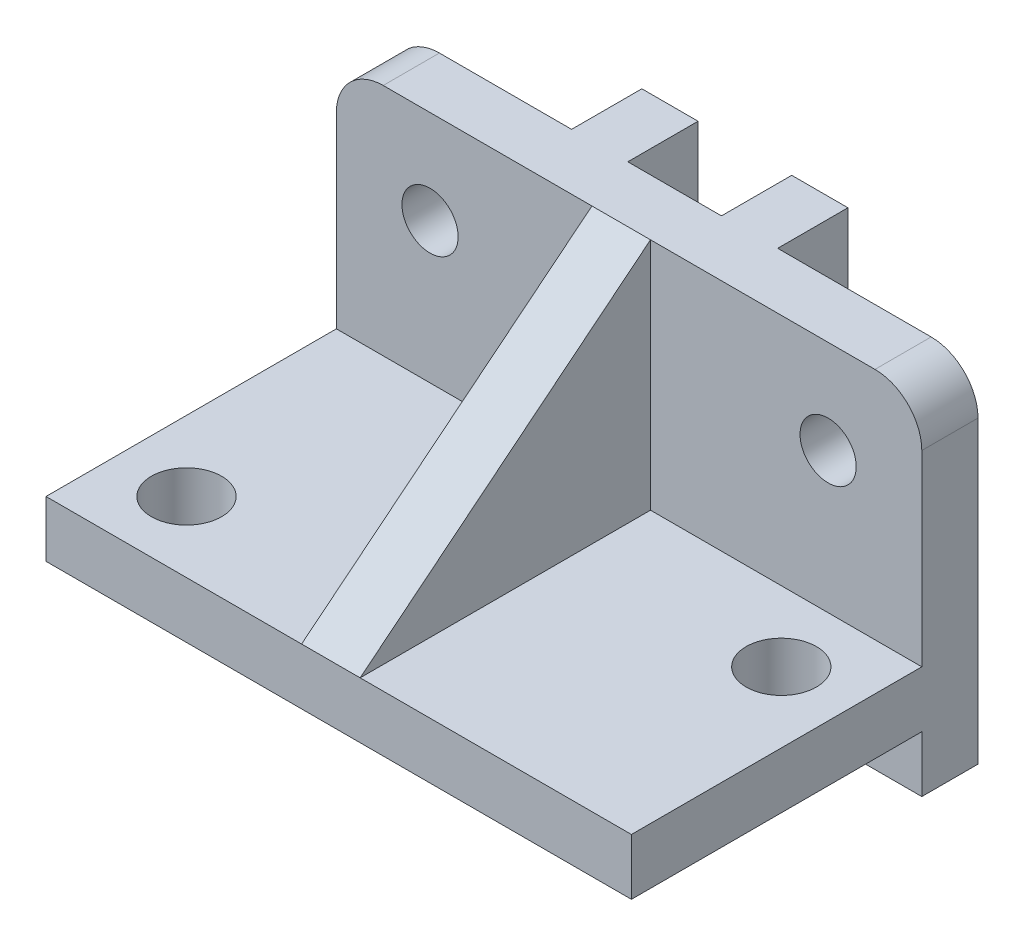
SolidWorks part; units mm, degrees
ref_plane "Front Plane" through (0, 0, 0) normal (0, 0, 1) x (1, 0, 0)
ref_plane "Top Plane" through (0, 0, 0) normal (0, 1, 0) x (1, 0, 0)
ref_plane "Right Plane" through (0, 0, 0) normal (1, 0, 0) x (0, 0, -1)
sketch "Sketch1" plane through (0, 0, 0) normal (0, 1, 0) x (1, 0, 0)
  line L0 (0, 0) -> (125, 0)
  line L1 (125, 0) -> (125, 62)
  line L2 (125, 62) -> (0, 62)
  line L3 (0, 62) -> (0, 0)
  circle A0 centre (15, 15) radius 7.5
  circle A1 centre (110, 47) radius 7.5
  dimension "D5" = 15
  dimension "D6" = 15
  dimension "D1" = 125
  dimension "D2" = 62
  dimension "D3" = 15
  dimension "D4" = 15
  dimension "D7" = 15
extrude "Boss-Extrude1" add sketch "Sketch1" along normal blind 12
sketch "Sketch2" plane through (125, 0, 0) normal (1, 0, 0) x (0, 0, -1)
  line L0 (62, 0) -> (62, -12)
  line L1 (62, -12) -> (74, -12)
  line L2 (74, -12) -> (74, 62)
  line L3 (74, 62) -> (62, 62)
  line L4 (62, 62) -> (62, 12)
  line L5 (0, 0) -> (62, 0) construction
  line L10 (0, 0) -> (62, 0)
  line L11 (62, 0) -> (62, 12)
  line L12 (62, 12) -> (0, 12)
  line L13 (0, 12) -> (0, 0)
  line L14 (0, 0) -> (62, 0)
  line L16 (62, 12) -> (0, 12)
  line L17 (0, 12) -> (0, 0)
  dimension "D1" = 12
  dimension "D2" = 12
  dimension "D3" = 74
  dimension "D4" = 0
extrude "Boss-Extrude3" add sketch "Sketch2" against normal blind 125 contours L14 L0 L1 L2 L3 L4 L16 L17
sketch "Sketch7" plane through (0, 0, -74) normal (0, 0, -1) x (-1, 0, 0)
  line L0 (-70.2262, 62) -> (-70.2262, -12)
  line L1 (0, 62) -> (-125, 62) construction
  line L2 (0, -12) -> (-125, -12) construction
  line L3 (-70.2262, -12) -> (-82.2262, -12)
  line L4 (-82.2262, -12) -> (-82.2262, 62)
  line L5 (-82.2262, 62) -> (-70.2262, 62)
  line L6 (-50.2262, 62) -> (-50.2262, -12)
  line L7 (-50.2262, -12) -> (-38.2262, -12)
  line L8 (-38.2262, -12) -> (-38.2262, 62)
  line L9 (-38.2262, 62) -> (-50.2262, 62)
  dimension "D1" = 12
  dimension "D2" = 12
  dimension "D3" = 20
extrude "Boss-Extrude6" add sketch "Sketch7" along normal blind 15
sketch "Sketch8" plane through (0, 0, -62) normal (0, 0, 1) x (1, 0, 0)
  line L0 (67.075, 62) -> (67.075, 12)
  line L1 (0, 62) -> (125, 62) construction
  line L2 (125, 12) -> (0, 12) construction
  line L3 (67.075, 12) -> (54.5716, 12)
  line L4 (0, 12) -> (125, 12) construction
  line L5 (54.5716, 12) -> (54.5716, 62)
  line L6 (54.5716, 62) -> (67.075, 62)
extrude "Boss-Extrude7" add sketch "Sketch8" along normal blind 62
sketch "Sketch9" plane through (67.075, 0, 0) normal (1, 0, 0) x (0, 0, -1)
  line L0 (0, 12) -> (62, 62)
  line L1 (62, 62) -> (0, 62)
  line L2 (0, 62) -> (0, 12)
extrude "Cut-Extrude1" cut sketch "Sketch9" against normal blind 62
fillet "Fillet1" radius 10 1 edges at (125, 62, -68)
fillet "Fillet2" radius 10 1 edges at (0, 62, -68)
sketch "Sketch10" plane through (0, 12, 0) normal (0, 1, 0) x (1, 0, 0)
  line L0 (0, 0) -> (54.5716, 0) construction
  line L1 (0, 62) -> (0, 0) construction
  line L2 (125, 62) -> (67.075, 62) construction
  line L3 (125, 0) -> (125, 62) construction
  circle A0 centre (15, 15) radius 7.5
  circle A1 centre (110, 47) radius 7.5
  dimension "D1" = 15
  dimension "D4" = 15
  dimension "D2" = 15
  dimension "D3" = 15
  dimension "D5" = 15
  dimension "D6" = 15
extrude "Cut-Extrude2" cut sketch "Sketch10" against normal blind 12 contours A0 | A1
sketch "Sketch11" plane through (0, 0, -62) normal (0, 0, 1) x (1, 0, 0)
  line L0 (125, 52) -> (125, 12) construction
  line L1 (125, 12) -> (67.075, 12) construction
  line L2 (0, 52) -> (0, 12) construction
  line L3 (0, 12) -> (54.5716, 12) construction
  circle A0 centre (105, 42) radius 6
  circle A1 centre (20, 42) radius 6
  point P12 (0, 0)
  dimension "D1" = 12
  dimension "D2" = 12
  dimension "D3" = 20
  dimension "D4" = 30
  dimension "D5" = 20
  dimension "D6" = 30
extrude "Cut-Extrude3" cut sketch "Sketch11" against normal blind 12
